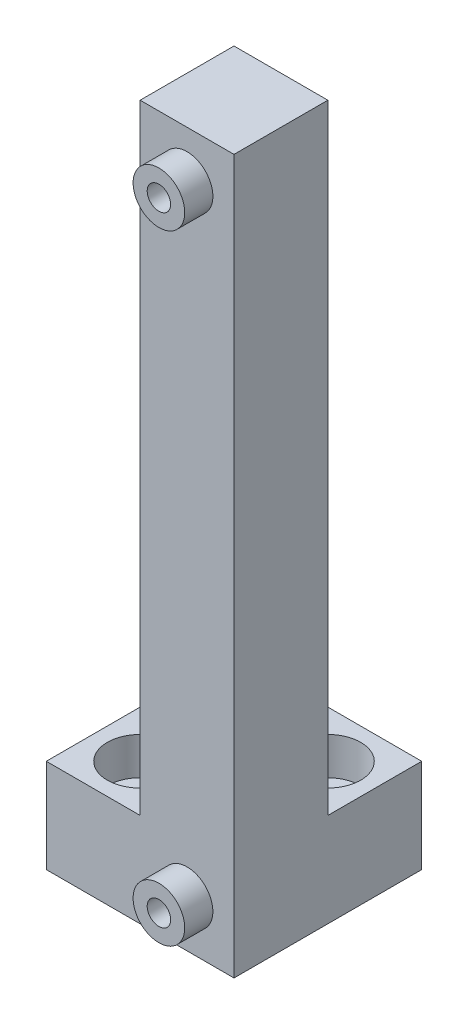
SolidWorks part; units mm, degrees
ref_plane "Plan de face" through (0, 0, 0) normal (0, 0, 1) x (1, 0, 0)
ref_plane "Plan de dessus" through (0, 0, 0) normal (0, 1, 0) x (1, 0, 0)
ref_plane "Plan de droite" through (0, 0, 0) normal (1, 0, 0) x (0, 0, -1)
sketch "Esquisse1" plane through (0, 0, 0) normal (0, 0, 1) x (1, 0, 0)
  line L0 (-10, 76) -> (0, 76)
  line L1 (0, 76) -> (0, 0)
  line L2 (0, 0) -> (-20, 0)
  line L3 (-20, 0) -> (-20, 10)
  line L4 (-20, 10) -> (-10, 10)
  line L5 (-10, 10) -> (-10, 76)
  dimension "D1" = 76
  dimension "D2" = 20
  dimension "D3" = 10
  dimension "D4" = 10
extrude "Boss.-Extru.1" add sketch "Esquisse1" along normal blind 10
sketch "Esquisse2" plane through (0, 0, 10) normal (0, 0, 1) x (1, 0, 0)
  line L0 (0, 76) -> (-10, 76) construction
  line L2 (-20, 0) -> (0, 0) construction
  circle A0 centre (-5, 71) radius 2.75
  circle A1 centre (-5, 5) radius 2.75
  point P7 (-5, 76)
  dimension "D1" = 5.5
  dimension "D2" = 5
  dimension "D3" = 5
extrude "Boss.-Extru.2" add sketch "Esquisse2" along normal blind 3
sketch "Esquisse3" plane through (0, 0, 13) normal (0, 0, 1) x (1, 0, 0)
  circle A0 centre (-5, 71) radius 1.25
  circle A1 centre (-5, 5) radius 1.25
  dimension "D1" = 2.5
extrude "Enlèv. mat.-Extru.1" cut sketch "Esquisse3" against normal blind 8
sketch "Esquisse4" plane through (0, 0, 0) normal (0, 0, -1) x (-1, 0, 0)
  line L0 (0, 0) -> (0, 76) construction
  line L1 (0, 10) -> (10, 10)
  line L2 (0, 10) -> (0, 0)
  line L3 (0, 0) -> (10, 0)
  line L4 (10, 10) -> (10, 0)
  line L5 (20, 0) -> (0, 0) construction
extrude "Boss.-Extru.3" add sketch "Esquisse4" along normal blind 10
sketch "Esquisse5" plane through (0, 10, 0) normal (0, 1, 0) x (1, 0, 0)
  line L0 (-10, 0) -> (-20, 0) construction
  line L1 (-20, -10) -> (-20, 0) construction
  line L2 (-10, 10) -> (-10, 0) construction
  line L3 (-10, 10) -> (0, 10) construction
  circle A0 centre (-15, -5) radius 1.75
  circle A1 centre (-5, 5) radius 1.75
  point P7 (-15, 0)
  point P10 (-20, -5)
  point P14 (-10, 5)
  point P18 (-5, 10)
  dimension "D1" = 3.5
extrude "Enlèv. mat.-Extru.2" cut sketch "Esquisse5" against normal up to next
sketch "Esquisse6" plane through (0, 10, 0) normal (0, 1, 0) x (1, 0, 0)
  circle A0 centre (-15, -5) radius 3.5
  circle A1 centre (-5, 5) radius 3.5
  dimension "D1" = 7
extrude "Enlèv. mat.-Extru.3" cut sketch "Esquisse6" against normal blind 4
